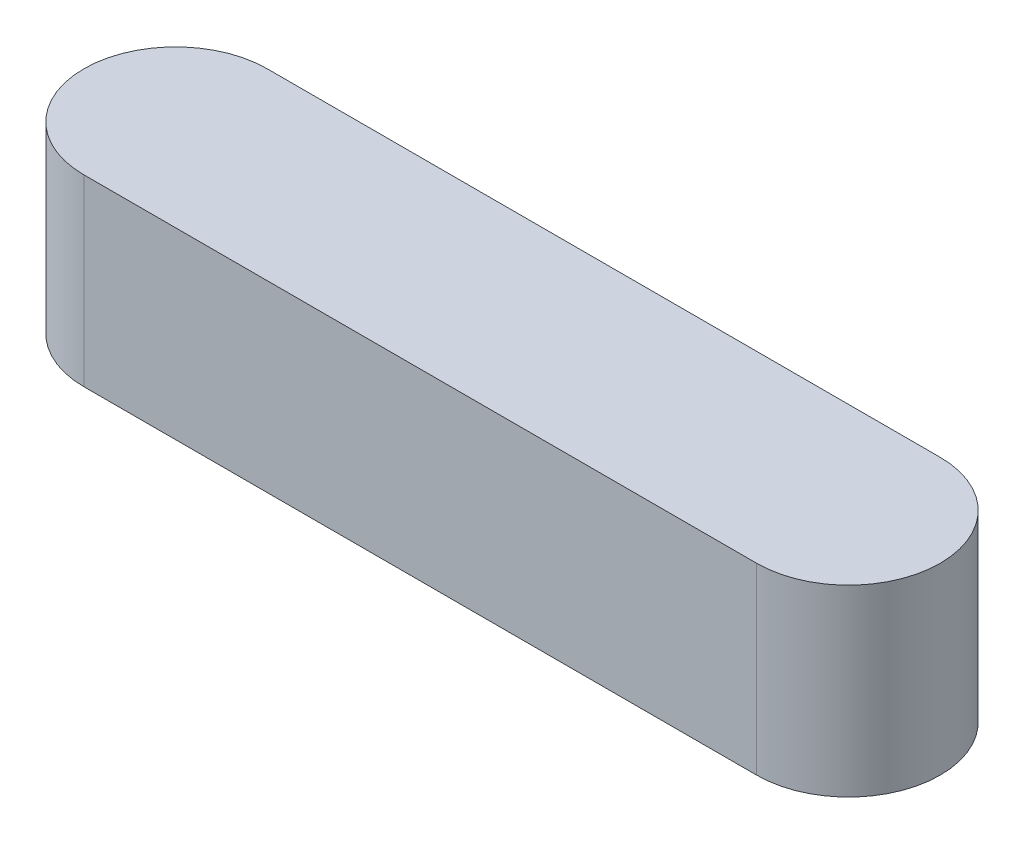
SolidWorks part; units mm, degrees
ref_plane "Спереди" through (0, 0, 0) normal (0, 0, 1) x (1, 0, 0)
ref_plane "Сверху" through (0, 0, 0) normal (0, 1, 0) x (1, 0, 0)
ref_plane "Справа" through (0, 0, 0) normal (1, 0, 0) x (0, 0, -1)
sketch "Эскиз1" plane through (0, 0, 0) normal (0, 1, 0) x (1, 0, 0)
  line L0 (0, 0) -> (22, 0) construction
  line L2 (0, 3) -> (22, 3)
  line L3 (0, -3) -> (22, -3)
  arc A0 (0, 3) -> (0, -3) centre (0, 0) ccw
  arc A1 (22, -3) -> (22, 3) centre (22, 0) ccw
  point P5 (11, 0)
extrude "Бобышка-Вытянуть1" add sketch "Эскиз1" along normal blind 6
